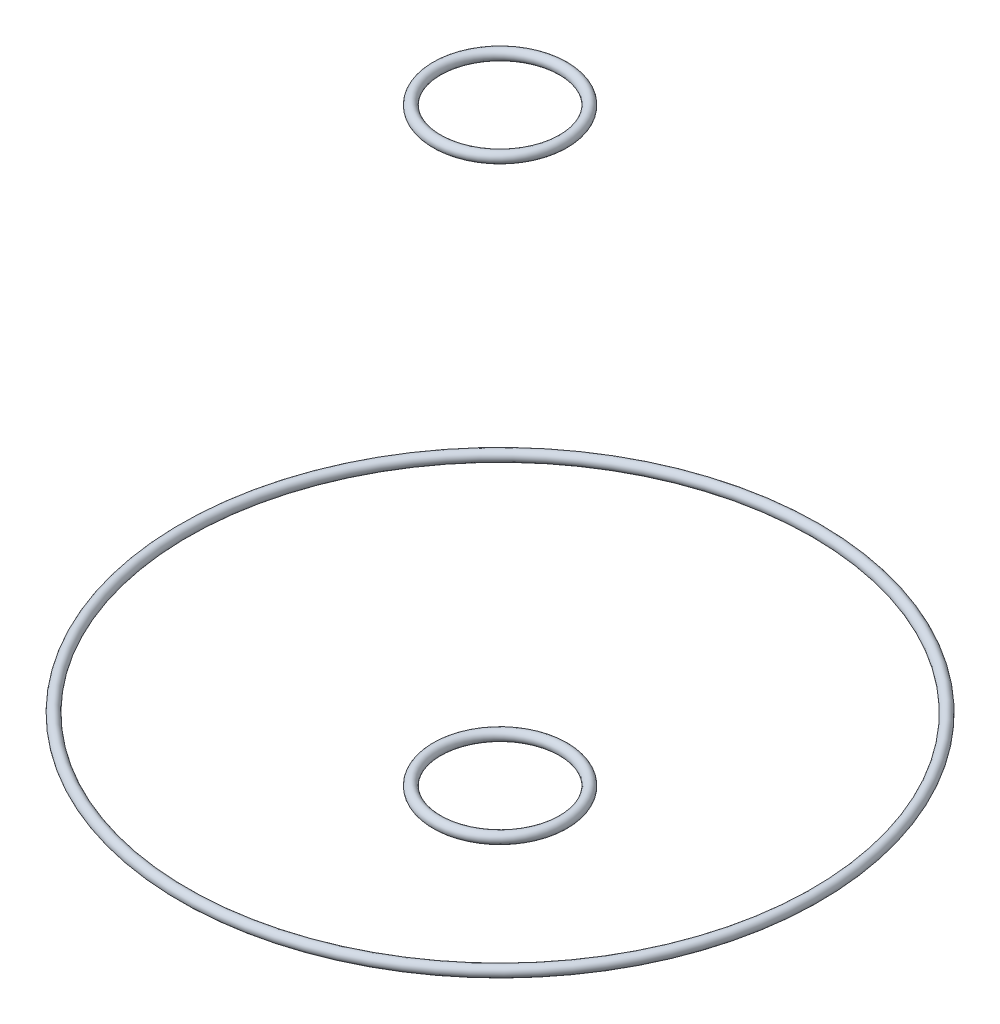
SolidWorks part; units mm, degrees
ref_plane "Front" through (0, 0, 0) normal (0, 0, 1) x (1, 0, 0)
ref_plane "Top" through (0, 0, 0) normal (0, 1, 0) x (1, 0, 0)
ref_plane "Right" through (0, 0, 0) normal (1, 0, 0) x (0, 0, -1)
sketch "Sketch1" plane through (0, 0, 0) normal (0, 0, 1) x (1, 0, 0)
  line L0 (0, 0) -> (0, 53.2994) construction
  circle A0 centre (762, 0) radius 12.7
  circle A1 centre (152.4, -152.4) radius 12.7
  circle A2 centre (152.4, 1270) radius 12.7
  dimension "D1" = 25.4
  dimension "D2" = 1524
  dimension "D3" = 304.8
  dimension "D4" = 1270
  dimension "D5" = 152.4
revolve "Revolve1" add sketch "Sketch1" angle 360 about L0
sketch "Sketch2" plane through (0, 0, 0) normal (0, 0, 1) x (1, 0, 0)
  line L0 (774.7, 0) -> (165.1, 1270) construction
  arc A0 (762, -12.7) -> (762, 12.7) centre (762, 0) ccw construction
  arc A1 (152.4, 1257.3) -> (152.4, 1282.7) centre (152.4, 1270) ccw construction
